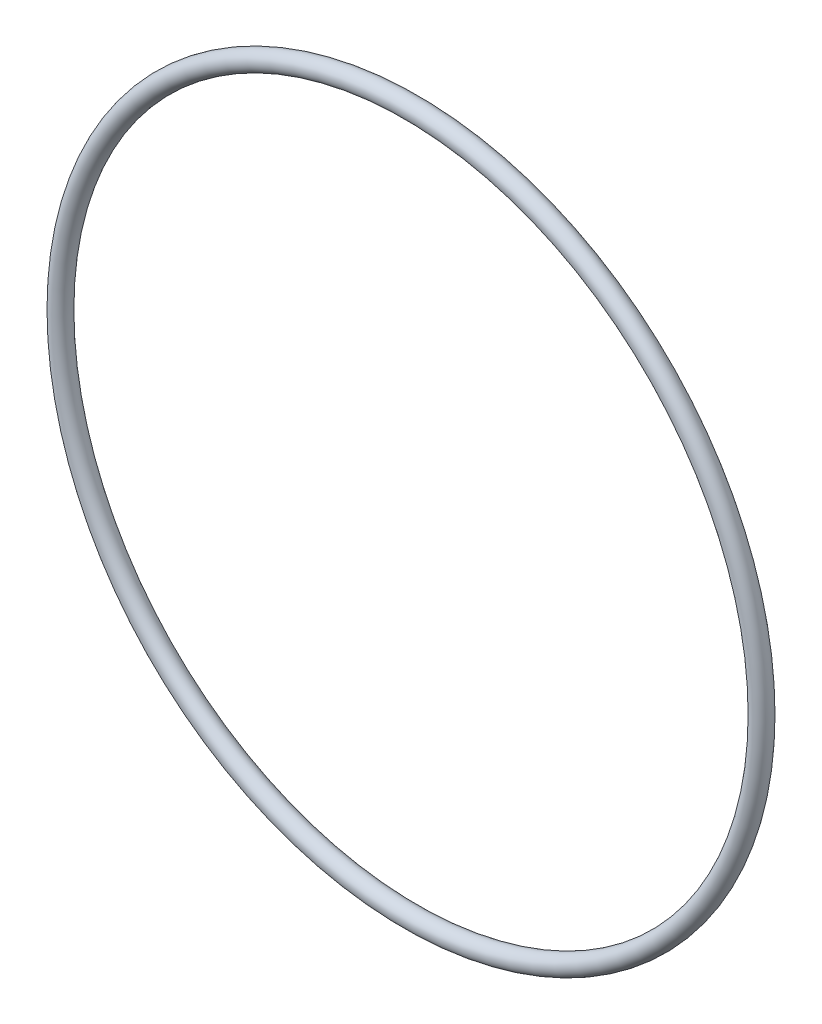
SolidWorks part; units mm, degrees
material "Rubber"
ref_plane "Front Plane" through (0, 0, 0) normal (0, 0, 1) x (1, 0, 0)
ref_plane "Top Plane" through (0, 0, 0) normal (0, 1, 0) x (1, 0, 0)
ref_plane "Right Plane" through (0, 0, 0) normal (1, 0, 0) x (0, 0, -1)
sketch "Sketch1" plane through (0, 0, 0) normal (0, 0, 1) x (1, 0, 0)
  line L0 (-66.8274, 0) -> (66.8274, 0) construction
  line L1 (-63.2968, 0) -> (63.2968, 0) construction
  line L2 (-47.2541, 47.2541) -> (47.2541, -47.2541) construction
  point P3 (63.2968, 0)
  point P4 (0, 0)
  point P8 (0, 0)
  point P9 (0, 0)
  point P10 (-66.8274, 0)
  point P11 (-63.2968, 0)
  point P14 (0, 0)
  point P15 (47.2541, -47.2541)
  point P16 (66.8274, 0)
  dimension "OD" = 133.6548
  dimension "ID" = 126.5936
  dimension "Width" = 3.5306
  dimension "D1" = 45
sketch "Sketch2" plane through (0, 0, 0) normal (0, 1, 0) x (1, 0, 0)
  line L0 (-66.8274, 0) -> (66.8274, 0) construction
  line L1 (-65.0621, 1.7653) -> (-65.0621, -1.7653) construction
  line L2 (0, -1.7653) -> (0, 1.7653) construction
  circle A0 centre (-65.0621, 0) radius 1.7653
  point P12 (0, 0)
revolve "Revolve1" add sketch "Sketch2" angle 360 about L2
sketch "Sketch3" plane through (0, 0, 0) normal (1, 0, 0) x (0, 0, -1)
  line L0 (-1.7653, 0) -> (1.7653, 0) construction
  line L1 (-1.7653, -47.4726) -> (-1.7653, 47.4726) construction
  point P4 (0, 0)
  point P7 (-1.7653, 0)
  point P9 (-1.7653, -47.4726)
  dimension "D1" = 3.5306
  dimension "D2" = 94.9452
equation "\"D1@Sketch3\" = \"Width@Sketch1\""
equation "\"D2@Sketch3\" = \"ID@Sketch1\" * .75"
